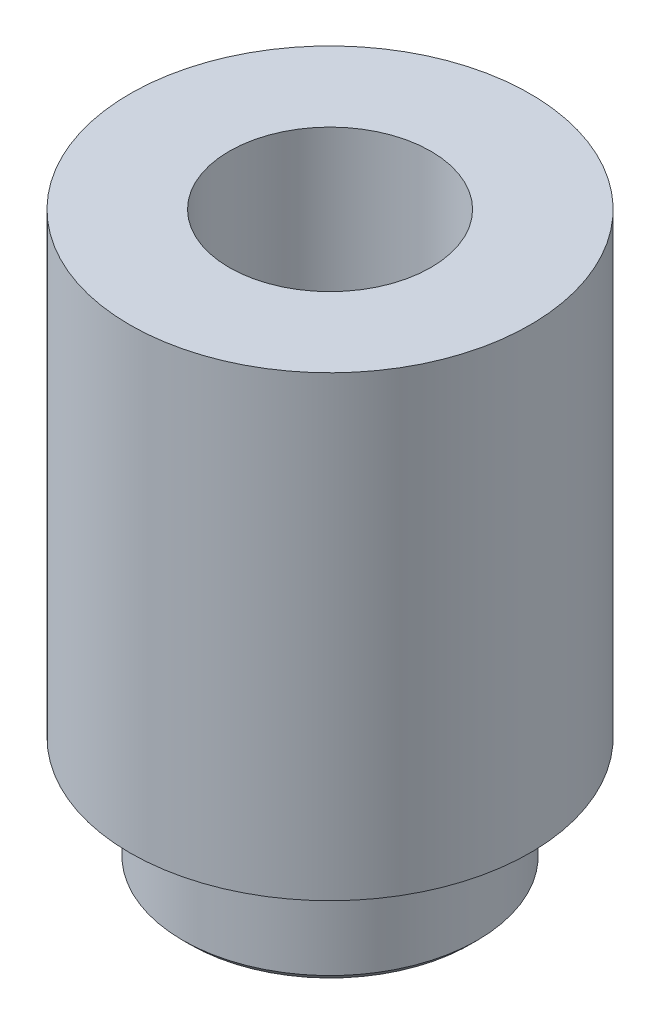
SolidWorks part; units mm, degrees
ref_plane "Front Plane" through (0, 0, 0) normal (0, 0, 1) x (1, 0, 0)
ref_plane "Top Plane" through (0, 0, 0) normal (0, 1, 0) x (1, 0, 0)
ref_plane "Right Plane" through (0, 0, 0) normal (1, 0, 0) x (0, 0, -1)
sketch "Sketch1" plane through (0, 0, 0) normal (0, 1, 0) x (1, 0, 0)
  circle A0 centre (0, 0) radius 1.4
  circle A1 centre (0, 0) radius 2.78
  dimension "D1" = 5.56
  dimension "D2" = 2.8
extrude "Boss-Extrude1" add sketch "Sketch1" along normal blind 6.35
sketch "Sketch2" plane through (0, 0, 0) normal (0, -1, 0) x (1, 0, 0)
  circle A0 centre (0, 0) radius 1.4
  circle A1 centre (0, 0) radius 2.045
  circle A2 centre (0, 0) radius 1.4 construction
  dimension "D1" = 4.09
extrude "Boss-Extrude2" add sketch "Sketch2" along normal blind 1.52
chamfer "Chamfer1" distance 0.1 angle 45 1 edges at (0, -1.52, -2.045)
